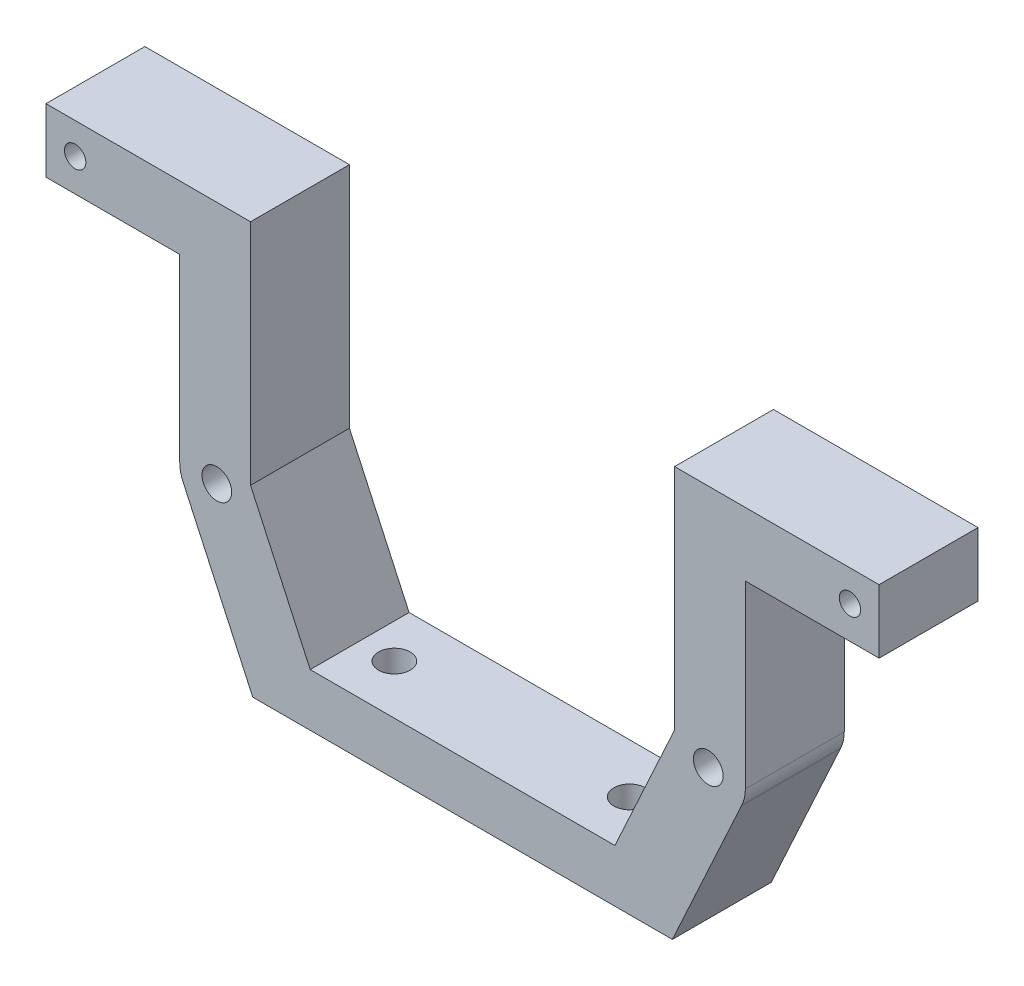
SolidWorks part; units mm, degrees
ref_plane "Front Plane" through (0, 0, 0) normal (0, 0, 1) x (1, 0, 0)
ref_plane "Top Plane" through (0, 0, 0) normal (0, 1, 0) x (1, 0, 0)
ref_plane "Right Plane" through (0, 0, 0) normal (1, 0, 0) x (0, 0, -1)
sketch "Sketch1" plane through (0, 0, 0) normal (0, 0, 1) x (1, 0, 0)
  line L0 (-27.2258, 10.9693) -> (-19.5649, -5.6956)
  line L1 (-26.944, -12.4521) -> (-35.8252, 6.8675)
  line L2 (-36.3189, 8.9793) -> (-36.3189, 32.0981)
  line L3 (0, -33.4207) -> (0, 86.0206) construction
  line L4 (53.4925, 32.0981) -> (53.4925, 40.2784)
  line L5 (-27.2258, 40.2784) -> (-27.2258, 10.9693)
  line L6 (26.944, -12.4521) -> (35.8252, 6.8675)
  line L7 (27.2258, 10.9693) -> (19.5649, -5.6956)
  line L8 (-53.4925, 40.2784) -> (-27.2258, 40.2784)
  line L9 (36.3189, 32.0981) -> (53.4925, 32.0981)
  line L10 (53.4925, 40.2784) -> (27.2258, 40.2784)
  line L11 (27.2258, 40.2784) -> (27.2258, 10.9693)
  line L12 (36.3189, 8.9793) -> (36.3189, 32.0981)
  line L13 (-19.5649, -5.6956) -> (19.5649, -5.6956)
  line L14 (26.944, -12.4521) -> (-26.944, -12.4521)
  line L19 (-36.3189, 32.0981) -> (-53.4925, 32.0981)
  line L20 (-53.4925, 32.0981) -> (-53.4925, 40.2784)
  circle A0 centre (-49.7493, 36.2843) radius 1.3716
  circle A1 centre (49.7493, 36.2843) radius 1.3716
  circle A2 centre (31.5546, 8.9793) radius 1.905
  arc A3 (-36.3189, 8.9793) -> (-35.8252, 6.8675) centre (-31.5546, 8.9793) ccw
  arc A4 (36.3189, 8.9793) -> (35.8252, 6.8675) centre (31.5546, 8.9793) cw
  circle A7 centre (-31.5546, 8.9793) radius 1.905
  point P11 (0, -1.0886)
  point P14 (0, 47.7615)
  point P23 (0, -12.6049)
  point P24 (0, 39.5222)
  point P26 (0, -75.2646)
  point P27 (0, -12.6049)
  point P31 (0, -12.6049)
  point P32 (0, 13.5908)
  point P33 (0, 55.0155)
  point P34 (0, 68.8613)
  point P36 (0, -12.6049)
  point P37 (0, -57.9768)
  point P45 (0, -12.4521)
  point P47 (0, -5.6956)
  point P58 (0, -6.1605)
  point P67 (0, -12.4521)
  point P82 (0, 41.6075)
  dimension "D2" = 3.81
  dimension "D3" = 2.7432
extrude "Extrude1" add sketch "Sketch1" along normal blind 12.7
sketch "Sketch4" plane through (0, -12.4521, 0) normal (0, -1, 0) x (1, 0, 0)
  line L0 (-21.5096, 6.4496) -> (-21.5096, 21.9705) construction
  line L1 (-21.5096, 6.4496) -> (0, 6.4496) construction
  line L3 (0, 0) -> (0, 26.9197) construction
  circle A0 centre (-21.5096, 6.4496) radius 3.175
  circle A1 centre (21.5096, 6.4496) radius 3.175
  dimension "D1" = 6.35
sketch "Sketch2" plane through (0, -12.4521, 0) normal (0, -1, 0) x (1, 0, 0)
  line L0 (0, 32.4456) -> (0, -21.6182) construction
  circle A0 centre (15.1051, 6.35) radius 2.032
  circle A1 centre (-15.1051, 6.35) radius 2.032
  dimension "D1" = 4.064
extrude "Extrude2" cut sketch "Sketch2" against normal blind 9.652
ref_plane "Mid PLane" through (0, 0, 6.35) normal (0, 0, 1) x (1, 0, 0)
